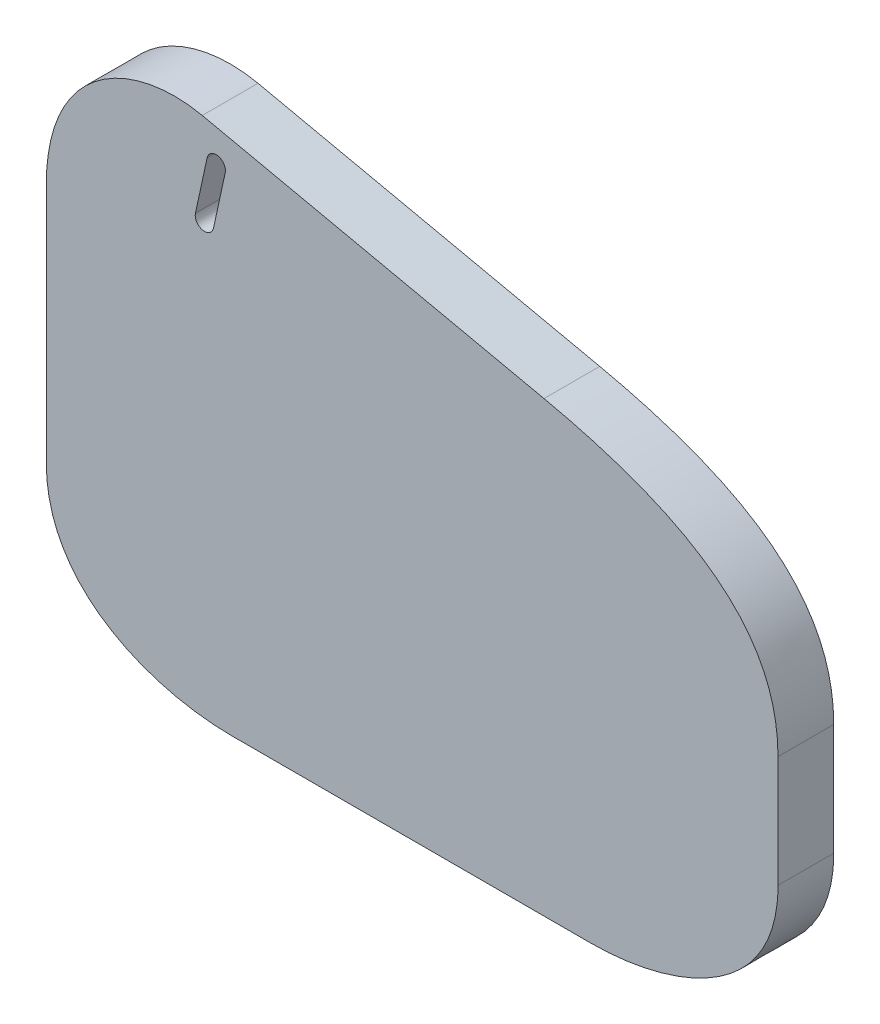
SolidWorks part; units mm, degrees
ref_plane "Спереди" through (0, 0, 0) normal (0, 0, 1) x (1, 0, 0)
ref_plane "Сверху" through (0, 0, 0) normal (0, 1, 0) x (1, 0, 0)
ref_plane "Справа" through (0, 0, 0) normal (1, 0, 0) x (0, 0, -1)
sketch "Эскиз1_fr" plane through (0, 0, 0) normal (0, 0, 1) x (1, 0, 0)
  line L0 (0, 0) -> (0, 20)
  line L1 (-41.9869, 54.6497) -> (-103.3012, 67.9789)
  line L2 (-131.2925, 43.0977) -> (-131.2925, 0)
  line L3 (-33.5451, -25.7698) -> (-97.9695, -25.7698)
  spline S0 degree 3 poles (0, 20) (0, 38.146) (-14.2095, 48.6111) (-41.9869, 54.6497) knots 0 0 0 0 1 1 1 1
  spline S1 degree 3 poles (-103.3012, 67.9789) (-115.5, 70.6308) (-131.2925, 63.3933) (-131.2925, 43.0977) knots 0 0 0 0 1 1 1 1
  spline S2 degree 3 poles (-33.5451, -25.7698) (-19.4449, -25.7698) (0, -19.0638) (0, 0) knots 0 0 0 0 1 1 1 1
  spline S3 degree 3 poles (-97.9695, -25.7698) (-112.0112, -25.7698) (-131.2925, -19.0252) (-131.2925, 0) knots 0 0 0 0 1 1 1 1
  dimension "D1" = 20
extrude "Бобышка-Вытянуть1" add sketch "Эскиз1_fr" along normal blind 10
sketch "Эскиз2_fr" plane through (0, 0, 0) normal (0, 0, -1) x (-1, 0, 0)
  line L2 (100.8084, 61.4805) -> (102.9069, 51.8273) construction
  line L3 (102.4293, 61.8329) -> (104.5278, 52.1796)
  line L4 (99.1876, 61.1282) -> (101.2861, 51.4749)
  arc A0 (102.4293, 61.8329) -> (99.1876, 61.1282) centre (100.8084, 61.4805) ccw
  arc A1 (101.2861, 51.4749) -> (104.5278, 52.1796) centre (102.9069, 51.8273) ccw
  point P4 (101.8577, 56.6539)
extrude "Вырез-Вытянуть1" cut sketch "Эскиз2_fr" against normal through all contours L3 A1 L4 A0
